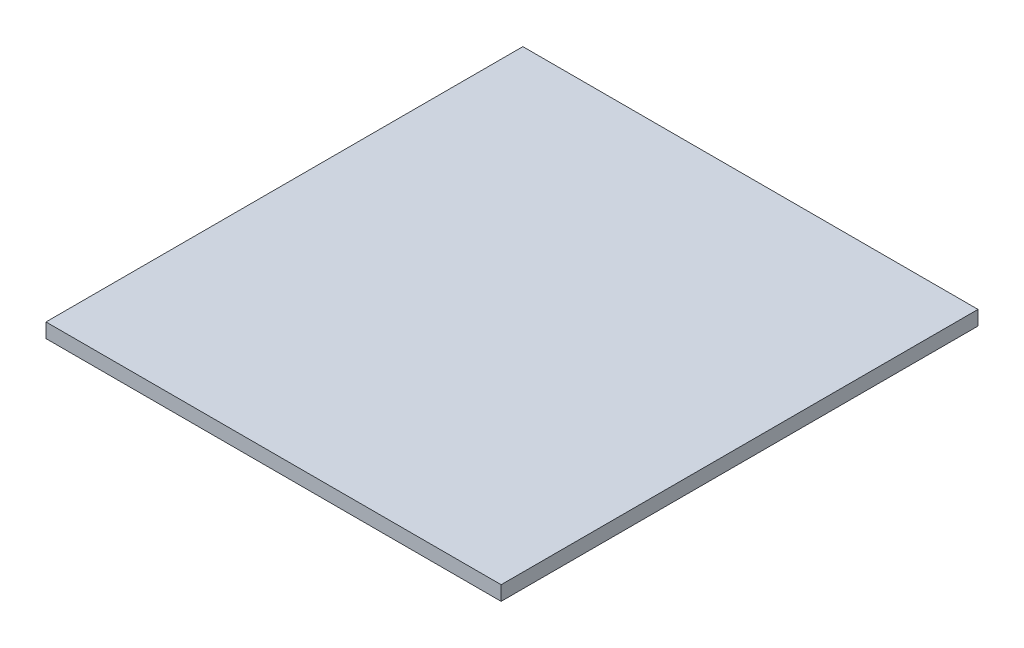
SolidWorks part; units mm, degrees
material "PE High Density"
ref_plane "Front Plane" through (0, 0, 0) normal (0, 0, 1) x (1, 0, 0)
ref_plane "Top Plane" through (0, 0, 0) normal (0, 1, 0) x (1, 0, 0)
ref_plane "Right Plane" through (0, 0, 0) normal (1, 0, 0) x (0, 0, -1)
sketch "Sketch1" plane through (0, 0, 0) normal (0, 1, 0) x (1, 0, 0)
  line L1 (-100, -104.775) -> (100, -104.775)
  line L2 (-100, -104.775) -> (-100, 104.775)
  line L3 (-100, 104.775) -> (100, 104.775)
  line L4 (100, -104.775) -> (100, 104.775)
  line L5 (-100, -104.775) -> (100, 104.775) construction
  line L6 (-100, 104.775) -> (100, -104.775) construction
  point P0 (0, 0)
  dimension "D1" = 200
  dimension "D2" = 209.55
extrude "Boss-Extrude1" add sketch "Sketch1" along normal mid plane 6.35
equation "\"D2@Sketch1\"=8.25in"
equation "\"D1@Boss-Extrude1\"=0.25in"
